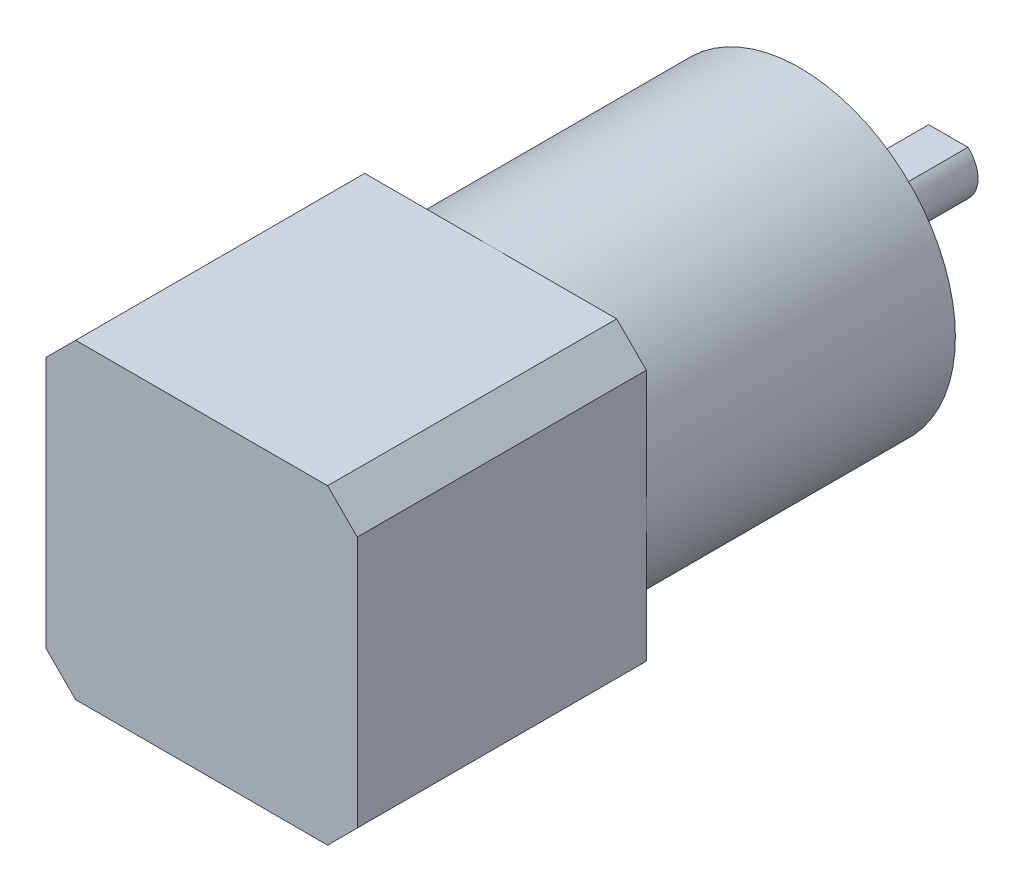
SolidWorks part; units mm, degrees
ref_plane "Front Plane" through (0, 0, 0) normal (0, 0, 1) x (1, 0, 0)
ref_plane "Top Plane" through (0, 0, 0) normal (0, 1, 0) x (1, 0, 0)
ref_plane "Right Plane" through (0, 0, 0) normal (1, 0, 0) x (0, 0, -1)
sketch "Sketch1" plane through (0, 0, 0) normal (0, 0, 1) x (1, 0, 0)
  line L1 (-21, 21) -> (21, 21)
  line L2 (-21, 21) -> (-21, -21)
  line L3 (-21, -21) -> (21, -21)
  line L4 (21, 21) -> (21, -21)
  line L5 (-21, 21) -> (21, -21) construction
  line L6 (-21, -21) -> (21, 21) construction
  point P0 (0, 0)
  dimension "D1" = 42
  dimension "D2" = 42
extrude "Boss-Extrude1" add sketch "Sketch1" along normal blind 39
chamfer "Chamfer1" distance 4 angle 45 4 edges at (-21, -21, 19.5) (21, -21, 19.5) (-21, 21, 19.5) (21, 21, 19.5)
sketch "Sketch2" plane through (0, 0, 0) normal (0, 0, -1) x (-1, 0, 0)
  circle A0 centre (0, 0) radius 20.95
  dimension "D1" = 41.9
extrude "Boss-Extrude2" add sketch "Sketch2" along normal blind 41.75
sketch "Sketch3" plane through (0, 0, -41.75) normal (0, 0, -1) x (-1, 0, 0)
  circle A0 centre (0, 0) radius 4
  dimension "D1" = 8
extrude "Boss-Extrude3" add sketch "Sketch3" along normal blind 20
sketch "Sketch4" plane through (0, 0, -61.75) normal (0, 0, -1) x (-1, 0, 0)
  line L1 (-2.6458, 3) -> (2.6458, 3)
  arc A2 (2.6458, 3) -> (-2.6458, 3) centre (0, 0) ccw
  dimension "D1" = 3
extrude "Cut-Extrude1" cut sketch "Sketch4" against normal blind 15
sketch "Sketch5" plane through (0, 0, -41.75) normal (0, 0, -1) x (-1, 0, 0)
  line L0 (0, 0) -> (12.0208, 12.0208) construction
  circle A0 centre (0, 0) radius 17 construction
  circle A1 centre (12.0208, 12.0208) radius 2
  circle A2 centre (12.0208, -12.0208) radius 2
  circle A3 centre (-12.0208, -12.0208) radius 2
  circle A4 centre (-12.0208, 12.0208) radius 2
  point P14 (0, 0)
  dimension "D1" = 4
extrude "Cut-Extrude2" cut sketch "Sketch5" against normal blind 20
